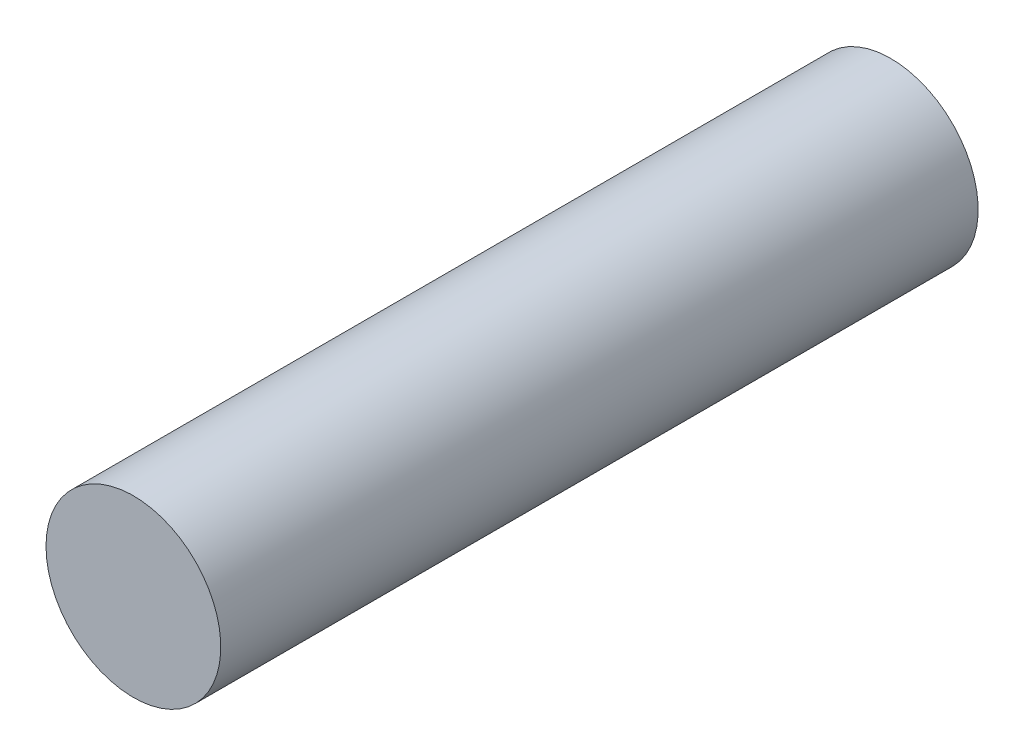
SolidWorks part; units mm, degrees
ref_plane "정면" through (0, 0, 0) normal (0, 0, 1) x (1, 0, 0)
ref_plane "윗면" through (0, 0, 0) normal (0, 1, 0) x (1, 0, 0)
ref_plane "우측면" through (0, 0, 0) normal (1, 0, 0) x (0, 0, -1)
sketch "스케치1" plane through (0, 0, 0) normal (0, 0, 1) x (1, 0, 0)
  circle A0 centre (0, 0) radius 1.5
  dimension "D1" = 3
extrude "보스-돌출1" add sketch "스케치1" along normal mid plane 13
